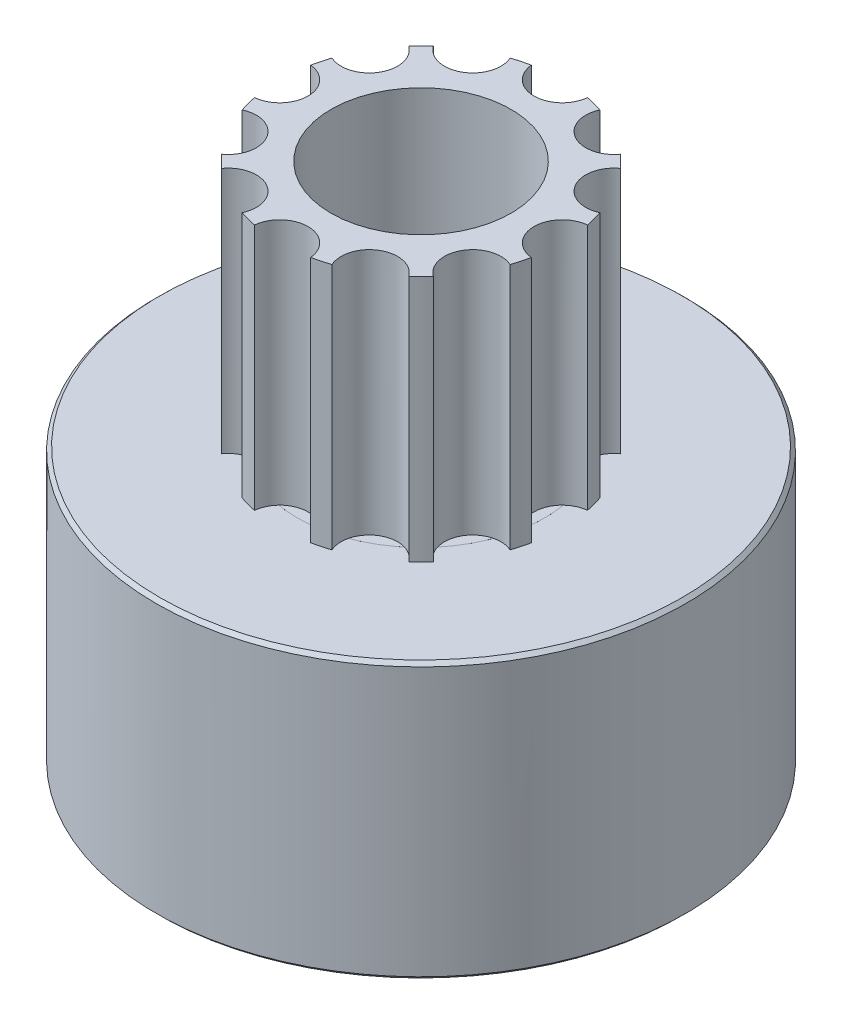
SolidWorks part; units mm, degrees
material "6061 slitina"
ref_plane "Přední rovina" through (0, 0, 0) normal (0, 0, 1) x (1, 0, 0)
ref_plane "Horní rovina" through (0, 0, 0) normal (0, 1, 0) x (1, 0, 0)
ref_plane "Pravá rovina" through (0, 0, 0) normal (1, 0, 0) x (0, 0, -1)
sketch "Skica1" plane through (0, 0, 0) normal (0, 1, 0) x (1, 0, 0)
  circle A0 centre (0, 0) radius 2.5
  arc B0 (-5.7301, 1.0983) -> (-5.3872, 2.2403) centre (-5.6803, 1.7058) ccw
  arc B1 (-5.7301, 1.0983) -> (-5.922, 1.0859) centre (-5.7841, 0.4401) ccw
  arc B2 (-5.922, 1.0859) -> (-6.0197, 1.0387) centre (-5.8743, 0.8624) ccw
  arc B3 (-6.0197, 1.0387) -> (-6.0791, 0.6004) centre (0, 0) ccw
  arc B4 (-6.0791, 0.6004) -> (-5.9974, 0.5289) centre (-5.892, 0.7317) ccw
  arc B5 (-5.9974, 0.5289) -> (-5.8158, 0.466) centre (-5.6927, 1.1148) ccw
  arc B6 (-5.7891, -0.7262) -> (-5.8158, 0.466) centre (-5.9294, -0.133) ccw
  arc B7 (-5.7891, -0.7262) -> (-5.9677, -0.7972) centre (-5.637, -1.3689) ccw
  arc B8 (-5.9677, -0.7972) -> (-6.0461, -0.8723) centre (-5.8532, -0.9951) ccw
  arc B9 (-6.0461, -0.8723) -> (-5.9671, -1.3075) centre (0, 0) ccw
  arc B10 (-5.9671, -1.3075) -> (-5.8673, -1.3503) centre (-5.8297, -1.1248) ccw
  arc B11 (-5.8673, -1.3503) -> (-5.6751, -1.354) centre (-5.7586, -0.6989) ccw
  arc B12 (-5.2813, -2.4796) -> (-5.6751, -1.354) centre (-5.5981, -1.9587) ccw
  arc B13 (-5.2813, -2.4796) -> (-5.4293, -2.6023) centre (-4.9381, -3.0438) ccw
  arc B14 (-5.4293, -2.6023) -> (-5.4806, -2.698) centre (-5.2593, -2.7551) ccw
  arc B15 (-5.4806, -2.698) -> (-5.271, -3.0875) centre (0, 0) ccw
  arc B16 (-5.271, -3.0875) -> (-5.1629, -3.0973) centre (-5.1968, -2.8713) ccw
  arc B17 (-5.1629, -3.0973) -> (-4.979, -3.0415) centre (-5.2608, -2.4442) ccw
  arc B18 (-4.2566, -3.9902) -> (-4.979, -3.0415) centre (-4.7188, -3.5928) ccw
  arc B19 (-4.2566, -3.9902) -> (-4.3594, -4.1527) centre (-3.7559, -4.4208) ccw
  arc B20 (-4.3594, -4.1527) -> (-4.3786, -4.2595) centre (-4.1505, -4.2455) ccw
  arc B21 (-4.3786, -4.2595) -> (-4.059, -4.5652) centre (0, 0) ccw
  arc B22 (-4.059, -4.5652) -> (-3.9531, -4.5412) centre (-4.0552, -4.3366) ccw
  arc B23 (-3.9531, -4.5412) -> (-3.7954, -4.4312) centre (-4.248, -3.9503) ccw
  arc B24 (-2.8152, -5.1103) -> (-3.7954, -4.4312) centre (-3.3776, -4.8751) ccw
  arc B25 (-2.8152, -5.1103) -> (-2.8628, -5.2965) centre (-2.2059, -5.3651) ccw
  arc B26 (-2.8628, -5.2965) -> (-2.8481, -5.4041) centre (-2.6354, -5.3203) ccw
  arc B27 (-2.8481, -5.4041) -> (-2.4496, -5.596) centre (0, 0) ccw
  arc B28 (-2.4496, -5.596) -> (-2.3563, -5.5405) centre (-2.5166, -5.3775) ccw
  arc B29 (-2.3563, -5.5405) -> (-2.2403, -5.3872) centre (-2.8194, -5.0696) ccw
  arc B30 (-1.0983, -5.7301) -> (-2.2403, -5.3872) centre (-1.7058, -5.6803) ccw
  arc B31 (-1.0983, -5.7301) -> (-1.0859, -5.922) centre (-0.4401, -5.7841) ccw
  arc B32 (-1.0859, -5.922) -> (-1.0387, -6.0197) centre (-0.8624, -5.8743) ccw
  arc B33 (-1.0387, -6.0197) -> (-0.6004, -6.0791) centre (0, 0) ccw
  arc B34 (-0.6004, -6.0791) -> (-0.5289, -5.9974) centre (-0.7317, -5.892) ccw
  arc B35 (-0.5289, -5.9974) -> (-0.466, -5.8158) centre (-1.1148, -5.6927) ccw
  arc B36 (0.7262, -5.7891) -> (-0.466, -5.8158) centre (0.133, -5.9294) ccw
  arc B37 (0.7262, -5.7891) -> (0.7972, -5.9677) centre (1.3689, -5.637) ccw
  arc B38 (0.7972, -5.9677) -> (0.8723, -6.0461) centre (0.9951, -5.8532) ccw
  arc B39 (0.8723, -6.0461) -> (1.3075, -5.9671) centre (0, 0) ccw
  arc B40 (1.3075, -5.9671) -> (1.3503, -5.8673) centre (1.1248, -5.8297) ccw
  arc B41 (1.3503, -5.8673) -> (1.354, -5.6751) centre (0.6989, -5.7586) ccw
  arc B42 (2.4796, -5.2813) -> (1.354, -5.6751) centre (1.9587, -5.5981) ccw
  arc B43 (2.4796, -5.2813) -> (2.6023, -5.4293) centre (3.0438, -4.9381) ccw
  arc B44 (2.6023, -5.4293) -> (2.698, -5.4806) centre (2.7551, -5.2593) ccw
  arc B45 (2.698, -5.4806) -> (3.0875, -5.271) centre (0, 0) ccw
  arc B46 (3.0875, -5.271) -> (3.0973, -5.1629) centre (2.8713, -5.1968) ccw
  arc B47 (3.0973, -5.1629) -> (3.0415, -4.979) centre (2.4442, -5.2608) ccw
  arc B48 (3.9902, -4.2566) -> (3.0415, -4.979) centre (3.5928, -4.7188) ccw
  arc B49 (3.9902, -4.2566) -> (4.1527, -4.3594) centre (4.4208, -3.7559) ccw
  arc B50 (4.1527, -4.3594) -> (4.2595, -4.3786) centre (4.2455, -4.1505) ccw
  arc B51 (4.2595, -4.3786) -> (4.5652, -4.059) centre (0, 0) ccw
  arc B52 (4.5652, -4.059) -> (4.5412, -3.9531) centre (4.3366, -4.0552) ccw
  arc B53 (4.5412, -3.9531) -> (4.4312, -3.7954) centre (3.9503, -4.248) ccw
  arc B54 (5.1103, -2.8152) -> (4.4312, -3.7954) centre (4.8751, -3.3776) ccw
  arc B55 (5.1103, -2.8152) -> (5.2965, -2.8628) centre (5.3651, -2.2059) ccw
  arc B56 (5.2965, -2.8628) -> (5.4041, -2.8481) centre (5.3203, -2.6354) ccw
  arc B57 (5.4041, -2.8481) -> (5.596, -2.4496) centre (0, 0) ccw
  arc B58 (5.596, -2.4496) -> (5.5405, -2.3563) centre (5.3775, -2.5166) ccw
  arc B59 (5.5405, -2.3563) -> (5.3872, -2.2403) centre (5.0696, -2.8194) ccw
  arc B60 (5.7301, -1.0983) -> (5.3872, -2.2403) centre (5.6803, -1.7058) ccw
  arc B61 (5.7301, -1.0983) -> (5.922, -1.0859) centre (5.7841, -0.4401) ccw
  arc B62 (5.922, -1.0859) -> (6.0197, -1.0387) centre (5.8743, -0.8624) ccw
  arc B63 (6.0197, -1.0387) -> (6.0791, -0.6004) centre (0, 0) ccw
  arc B64 (6.0791, -0.6004) -> (5.9974, -0.5289) centre (5.892, -0.7317) ccw
  arc B65 (5.9974, -0.5289) -> (5.8158, -0.466) centre (5.6927, -1.1148) ccw
  arc B66 (5.7891, 0.7262) -> (5.8158, -0.466) centre (5.9294, 0.133) ccw
  arc B67 (5.7891, 0.7262) -> (5.9677, 0.7972) centre (5.637, 1.3689) ccw
  arc B68 (5.9677, 0.7972) -> (6.0461, 0.8723) centre (5.8532, 0.9951) ccw
  arc B69 (6.0461, 0.8723) -> (5.9671, 1.3075) centre (0, 0) ccw
  arc B70 (5.9671, 1.3075) -> (5.8673, 1.3503) centre (5.8297, 1.1248) ccw
  arc B71 (5.8673, 1.3503) -> (5.6751, 1.354) centre (5.7586, 0.6989) ccw
  arc B72 (5.2813, 2.4796) -> (5.6751, 1.354) centre (5.5981, 1.9587) ccw
  arc B73 (5.2813, 2.4796) -> (5.4293, 2.6023) centre (4.9381, 3.0438) ccw
  arc B74 (5.4293, 2.6023) -> (5.4806, 2.698) centre (5.2593, 2.7551) ccw
  arc B75 (5.4806, 2.698) -> (5.271, 3.0875) centre (0, 0) ccw
  arc B76 (5.271, 3.0875) -> (5.1629, 3.0973) centre (5.1968, 2.8713) ccw
  arc B77 (5.1629, 3.0973) -> (4.979, 3.0415) centre (5.2608, 2.4442) ccw
  arc B78 (4.2566, 3.9902) -> (4.979, 3.0415) centre (4.7188, 3.5928) ccw
  arc B79 (4.2566, 3.9902) -> (4.3594, 4.1527) centre (3.7559, 4.4208) ccw
  arc B80 (4.3594, 4.1527) -> (4.3786, 4.2595) centre (4.1505, 4.2455) ccw
  arc B81 (4.3786, 4.2595) -> (4.059, 4.5652) centre (0, 0) ccw
  arc B82 (4.059, 4.5652) -> (3.9531, 4.5412) centre (4.0552, 4.3366) ccw
  arc B83 (3.9531, 4.5412) -> (3.7954, 4.4312) centre (4.248, 3.9503) ccw
  arc B84 (2.8152, 5.1103) -> (3.7954, 4.4312) centre (3.3776, 4.8751) ccw
  arc B85 (2.8152, 5.1103) -> (2.8628, 5.2965) centre (2.2059, 5.3651) ccw
  arc B86 (2.8628, 5.2965) -> (2.8481, 5.4041) centre (2.6354, 5.3203) ccw
  arc B87 (2.8481, 5.4041) -> (2.4496, 5.596) centre (0, 0) ccw
  arc B88 (2.4496, 5.596) -> (2.3563, 5.5405) centre (2.5166, 5.3775) ccw
  arc B89 (2.3563, 5.5405) -> (2.2403, 5.3872) centre (2.8194, 5.0696) ccw
  arc B90 (1.0983, 5.7301) -> (2.2403, 5.3872) centre (1.7058, 5.6803) ccw
  arc B91 (1.0983, 5.7301) -> (1.0859, 5.922) centre (0.4401, 5.7841) ccw
  arc B92 (1.0859, 5.922) -> (1.0387, 6.0197) centre (0.8624, 5.8743) ccw
  arc B93 (1.0387, 6.0197) -> (0.6004, 6.0791) centre (0, 0) ccw
  arc B94 (0.6004, 6.0791) -> (0.5289, 5.9974) centre (0.7317, 5.892) ccw
  arc B95 (0.5289, 5.9974) -> (0.466, 5.8158) centre (1.1148, 5.6927) ccw
  arc B96 (-0.7262, 5.7891) -> (0.466, 5.8158) centre (-0.133, 5.9294) ccw
  arc B97 (-0.7262, 5.7891) -> (-0.7972, 5.9677) centre (-1.3689, 5.637) ccw
  arc B98 (-0.7972, 5.9677) -> (-0.8723, 6.0461) centre (-0.9951, 5.8532) ccw
  arc B99 (-0.8723, 6.0461) -> (-1.3075, 5.9671) centre (0, 0) ccw
  arc B100 (-1.3075, 5.9671) -> (-1.3503, 5.8673) centre (-1.1248, 5.8297) ccw
  arc B101 (-1.3503, 5.8673) -> (-1.354, 5.6751) centre (-0.6989, 5.7586) ccw
  arc B102 (-2.4796, 5.2813) -> (-1.354, 5.6751) centre (-1.9587, 5.5981) ccw
  arc B103 (-2.4796, 5.2813) -> (-2.6023, 5.4293) centre (-3.0438, 4.9381) ccw
  arc B104 (-2.6023, 5.4293) -> (-2.698, 5.4806) centre (-2.7551, 5.2593) ccw
  arc B105 (-2.698, 5.4806) -> (-3.0875, 5.271) centre (0, 0) ccw
  arc B106 (-3.0875, 5.271) -> (-3.0973, 5.1629) centre (-2.8713, 5.1968) ccw
  arc B107 (-3.0973, 5.1629) -> (-3.0415, 4.979) centre (-2.4442, 5.2608) ccw
  arc B108 (-3.9902, 4.2566) -> (-3.0415, 4.979) centre (-3.5928, 4.7188) ccw
  arc B109 (-3.9902, 4.2566) -> (-4.1527, 4.3594) centre (-4.4208, 3.7559) ccw
  arc B110 (-4.1527, 4.3594) -> (-4.2595, 4.3786) centre (-4.2455, 4.1505) ccw
  arc B111 (-4.2595, 4.3786) -> (-4.5652, 4.059) centre (0, 0) ccw
  arc B112 (-4.5652, 4.059) -> (-4.5412, 3.9531) centre (-4.3366, 4.0552) ccw
  arc B113 (-4.5412, 3.9531) -> (-4.4312, 3.7954) centre (-3.9503, 4.248) ccw
  arc B114 (-5.1103, 2.8152) -> (-4.4312, 3.7954) centre (-4.8751, 3.3776) ccw
  arc B115 (-5.1103, 2.8152) -> (-5.2965, 2.8628) centre (-5.3651, 2.2059) ccw
  arc B116 (-5.2965, 2.8628) -> (-5.4041, 2.8481) centre (-5.3203, 2.6354) ccw
  arc B117 (-5.4041, 2.8481) -> (-5.596, 2.4496) centre (0, 0) ccw
  arc B118 (-5.596, 2.4496) -> (-5.5405, 2.3563) centre (-5.3775, 2.5166) ccw
  arc B119 (-5.5405, 2.3563) -> (-5.3872, 2.2403) centre (-5.0696, 2.8194) ccw
  dimension "D1" = 5
sketch_block_instance "Blok1-1"
sketch_block "Blok1"
extrude "Přidat vysunutím1" add sketch "Skica1" along normal blind 7 from offset 7.8
sketch "Skica2" plane through (0, 7.8, 0) normal (0, -1, 0) x (1, 0, 0)
  circle A0 centre (0, 0) radius 3.5
  circle A1 centre (0, 0) radius 2.5 construction
  circle A2 centre (0, 0) radius 2.5
  dimension "D1" = 7
extrude "Přidat vysunutím2" add sketch "Skica2" along normal blind 7.8
sketch "Skica3" plane through (0, 14.8, 0) normal (0, 1, 0) x (1, 0, 0)
  circle A0 centre (0, 0) radius 3.5
  circle A1 centre (0, 0) radius 2.5 construction
  circle A2 centre (0, 0) radius 2.5
  dimension "D1" = 7
sketch "Skica5" plane through (0, 16, 0) normal (0, 1, 0) x (1, 0, 0)
  circle A0 centre (0, 0) radius 7.5
  circle A3 centre (0, 0) radius 3.5 construction
  circle A4 centre (0, 0) radius 3.5
  dimension "D1" = 15
sketch "Skica6" plane through (0, 0, 0) normal (0, -1, 0) x (1, 0, 0)
  circle A0 centre (0, 0) radius 7.5
  circle A1 centre (0, 0) radius 3.5 construction
  circle A2 centre (0, 0) radius 3.5
  circle A3 centre (0, 0) radius 7.5 construction
extrude "Přidat vysunutím5" add sketch "Skica6" against normal up to surface (7.8 mm away) separate body up to face at (0, 7.8, 0)
chamfer "Zkosení3" distance 0.1 angle 45 2 edges at (0, 0, -7.5) (0, 7.8, 7.5)
sketch "Sketch7" plane through (0, 0, 0) normal (0, -1, 0) x (1, 0, 0)
  circle A1 centre (0, 0) radius 4.05
  dimension "D1" = 8.1
sketch "Sketch8" plane through (0, 16, 0) normal (0, 1, 0) x (1, 0, 0)
  circle A0 centre (0, 0) radius 6.65
ref_plane "Plane1" through (0, 0, -7.5) normal (0, 0, -1) x (-1, 0, 0)
ref_plane "Plane2" through (-7.5, 0, 0) normal (-1, 0, 0) x (0, 0, 1)
sketch "Sketch19" plane through (0, 0, -7.5) normal (0, 0, -1) x (-1, 0, 0)
  line L0 (0, 0.1) -> (0, 7.7)
  line L1 (7.5, 0.1) -> (-7.5, 0.1) construction
  line L2 (7.5, 7.7) -> (-7.5, 7.7) construction
  circle A0 centre (0, 3.9) radius 1.5
extrude "Cut-Extrude6" cut sketch "Sketch19" against normal blind 8 contours A0
sketch "Sketch20" plane through (-7.5, 0, 0) normal (-1, 0, 0) x (0, 0, 1)
  line L0 (0, 0.1) -> (0, 7.7)
  line L1 (-7.5, 0.1) -> (7.5, 0.1) construction
  line L2 (7.5, 7.7) -> (-7.5, 7.7) construction
  circle A0 centre (0, 3.9) radius 1.5
extrude "Cut-Extrude7" cut sketch "Sketch20" against normal blind 8 contours A0
sketch "Sketch21" plane through (0, 16, 0) normal (0, 1, 0) x (1, 0, 0)
  circle A0 centre (0, 0) radius 2.55
extrude "Cut-Extrude8" cut sketch "Sketch21" against normal blind 30
sketch "Sketch22" plane through (0, 14.8, 0) normal (0, 1, 0) x (1, 0, 0)
  arc A5 (2.9968, 2.6493) -> (0.796, 3.92) centre (0, 0) ccw
  arc A8 (2.6493, -2.9968) -> (2.9968, -2.6493) centre (0, 0) ccw
  arc A9 (0.796, -3.92) -> (-0.796, -3.92) centre (0, -4) ccw
  arc A10 (-1.2707, -3.7928) -> (-2.6493, -2.9968) centre (-2, -3.4641) ccw
  arc A11 (-2.9968, -2.6493) -> (-3.7928, -1.2707) centre (-3.4641, -2) ccw
  arc A12 (-3.92, -0.796) -> (-3.92, 0.796) centre (-4, 0) ccw
  arc A13 (-3.7928, 1.2707) -> (-2.9968, 2.6493) centre (-3.4641, 2) ccw
  arc A14 (-2.6493, 2.9968) -> (-1.2707, 3.7928) centre (-2, 3.4641) ccw
  arc A15 (-0.796, 3.92) -> (0.796, 3.92) centre (0, 4) ccw
  arc A16 (1.2707, 3.7928) -> (2.6493, 2.9968) centre (2, 3.4641) ccw
  arc A17 (2.9968, 2.6493) -> (3.7928, 1.2707) centre (3.4641, 2) ccw
  arc A18 (3.92, 0.796) -> (3.92, -0.796) centre (4, 0) ccw
  arc A19 (3.7928, -1.2707) -> (2.9968, -2.6493) centre (3.4641, -2) ccw
  arc A20 (2.6493, -2.9968) -> (1.2707, -3.7928) centre (2, -3.4641) ccw
  arc A21 (0.796, -3.92) -> (1.2707, -3.7928) centre (0, 0) ccw
  arc A22 (-1.2707, -3.7928) -> (-0.796, -3.92) centre (0, 0) ccw
  arc A23 (-2.9968, -2.6493) -> (-2.6493, -2.9968) centre (0, 0) ccw
  arc A24 (-3.92, -0.796) -> (-3.7928, -1.2707) centre (0, 0) ccw
  arc A25 (-3.7928, 1.2707) -> (-3.92, 0.796) centre (0, 0) ccw
  arc A26 (-2.6493, 2.9968) -> (-2.9968, 2.6493) centre (0, 0) ccw
  arc A27 (-0.796, 3.92) -> (-1.2707, 3.7928) centre (0, 0) ccw
  arc A28 (3.92, 0.796) -> (3.7928, 1.2707) centre (0, 0) ccw
  arc A29 (3.7928, -1.2707) -> (3.92, -0.796) centre (0, 0) ccw
  circle A30 centre (0.6389, -0.4771) radius 8.4329
  point P31 (0, 0)
  dimension "D2" = 12
extrude "Cut-Extrude10" cut sketch "Sketch22" against normal blind 7 contours A30 A29 A19 A8 A20 A21 A9 A22 A10 A23 A11 A24 A12 A25 A13 A26 A14 A27 A15 A5 A17 A28 A18
sketch "Sketch23" plane through (0, 14.8, 0) normal (0, 1, 0) x (1, 0, 0)
  circle A0 centre (0, 0) radius 3.2
  circle A1 centre (2, 3.4641) radius 0.8
  arc A2 (2.9968, 2.6493) -> (0.796, 3.92) centre (0, 0) ccw construction
  arc M7 (2.9968, 2.6493) -> (0.796, 3.92) centre (0, 0) ccw
extrude "Cut-Extrude13" cut sketch "Sketch23" against normal blind 7 contours A1 M7 | A1 M7
